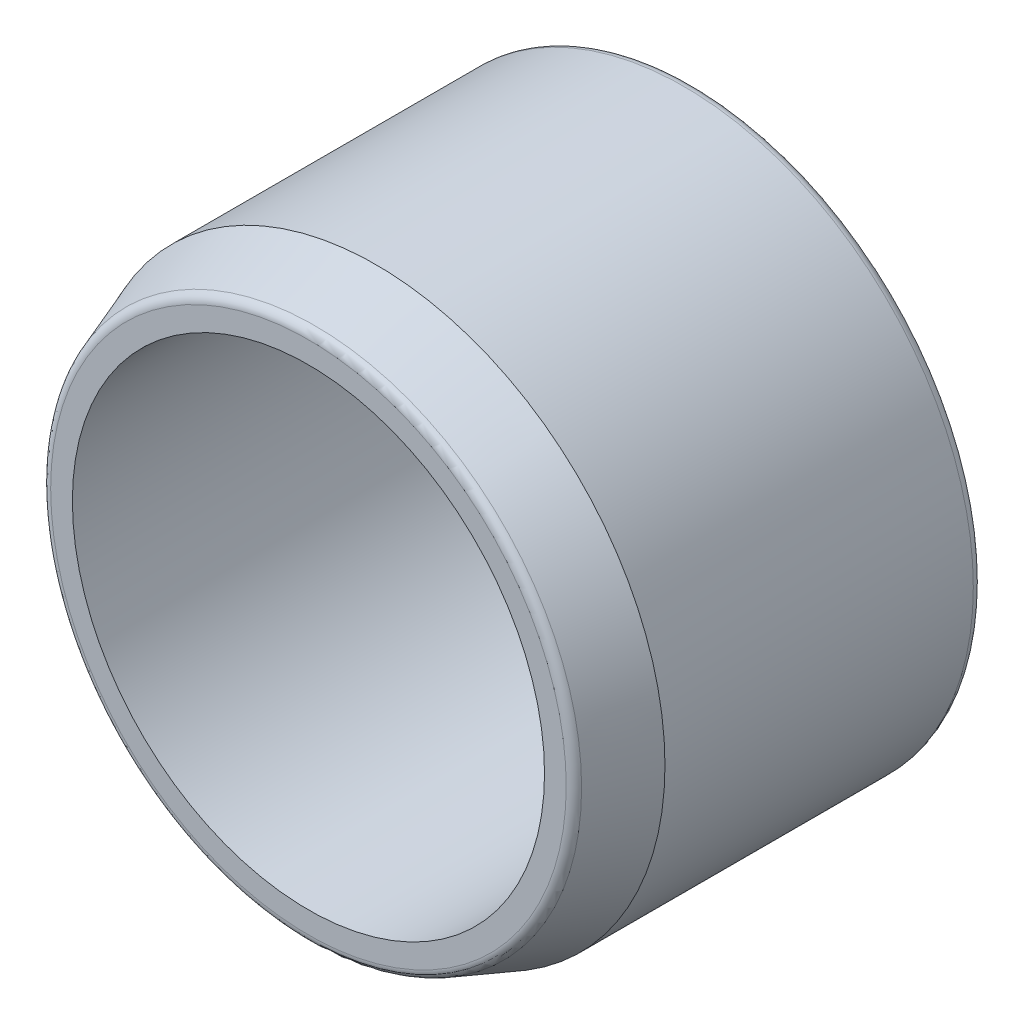
SolidWorks part; units mm, degrees
ref_plane "Front Plane" through (0, 0, 0) normal (0, 0, 1) x (1, 0, 0)
ref_plane "Top Plane" through (0, 0, 0) normal (0, 1, 0) x (1, 0, 0)
ref_plane "Right Plane" through (0, 0, 0) normal (1, 0, 0) x (0, 0, -1)
sketch "Sketch1" plane through (0, 0, 0) normal (0, 0, 1) x (1, 0, 0)
  circle A0 centre (0, 0) radius 24.5
  circle A1 centre (0, 0) radius 30
  dimension "D1" = 60
  dimension "D2" = 49
extrude "Boss-Extrude1" add sketch "Sketch1" along normal blind 40
chamfer "Chamfer1" distance 7 angle 20 1 edges at (30, 0, 40)
fillet "Fillet1" radius 1 2 edges at (30, 0, 0) (27.4522, 0, 40)
